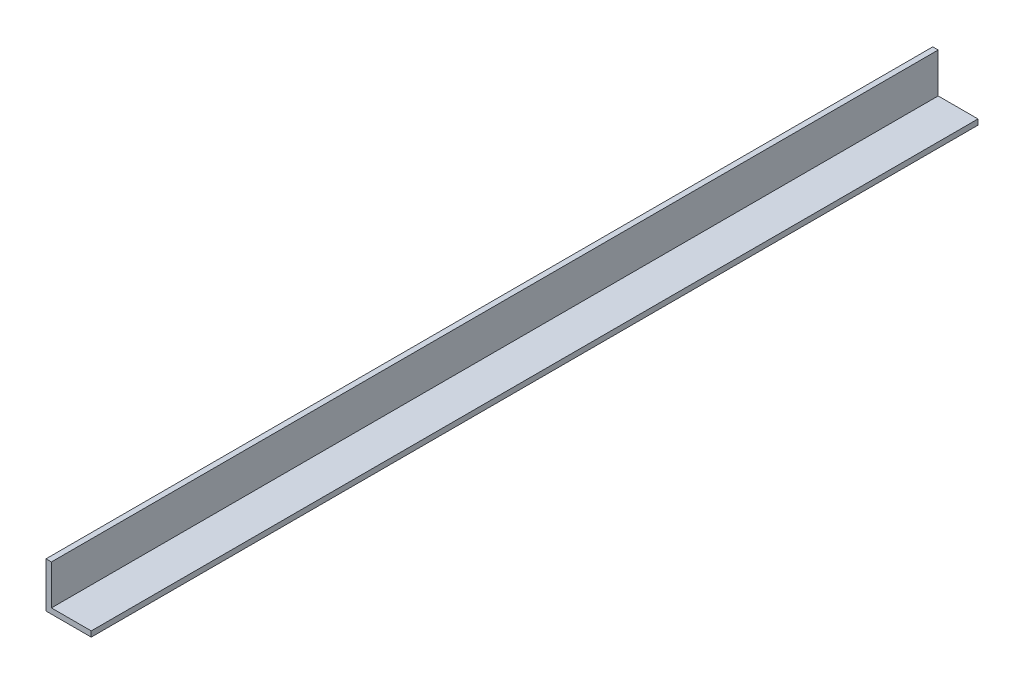
SolidWorks part; units mm, degrees
ref_plane "前视基准面" through (0, 0, 0) normal (0, 0, 1) x (1, 0, 0)
ref_plane "上视基准面" through (0, 0, 0) normal (0, 1, 0) x (1, 0, 0)
ref_plane "右视基准面" through (0, 0, 0) normal (1, 0, 0) x (0, 0, -1)
sketch "草图1" plane through (0, 0, 0) normal (0, 0, 1) x (1, 0, 0)
  line L1 (0, 0) -> (100, 0)
  line L2 (0, 0) -> (0, 100)
  line L3 (0, 100) -> (100, 100)
  line L4 (100, 0) -> (100, 100)
  dimension "D1" = 100
  dimension "D2" = 100
extrude "凸台-拉伸1" add sketch "草图1" along normal blind 1960
sketch "草图2" plane through (0, 0, 1960) normal (0, 0, 1) x (1, 0, 0)
  line L0 (0, 100) -> (0, 0) construction
  line L1 (100, 100) -> (12, 100)
  line L2 (100, 100) -> (100, 12)
  line L3 (100, 12) -> (12, 12)
  line L4 (12, 100) -> (12, 12)
  line L5 (0, 0) -> (100, 0) construction
  dimension "D1" = 12
  dimension "D2" = 12
extrude "切除-拉伸1" cut sketch "草图2" against normal through all
